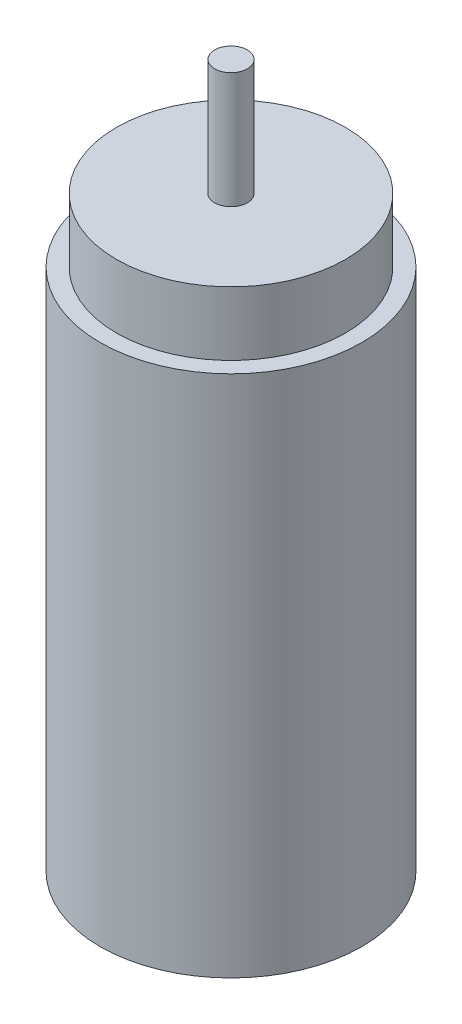
SolidWorks part; units mm, degrees
material "Vanadium"
ref_plane "Plan de face" through (0, 0, 0) normal (0, 0, 1) x (1, 0, 0)
ref_plane "Plan de dessus" through (0, 0, 0) normal (0, 1, 0) x (1, 0, 0)
ref_plane "Plan de droite" through (0, 0, 0) normal (1, 0, 0) x (0, 0, -1)
sketch "Sketch1" plane through (0, 0, 0) normal (0, 1, 0) x (1, 0, 0)
  circle A0 centre (0, 0) radius 4
  dimension "D1" = 8
extrude "Boss-Extrude1" add sketch "Sketch1" along normal blind 16
sketch "Sketch2" plane through (0, 16, 0) normal (0, 1, 0) x (1, 0, 0)
  circle A0 centre (0, 0) radius 3.5
  dimension "D1" = 7
extrude "Boss-Extrude2" add sketch "Sketch2" along normal blind 1.95
sketch "Sketch4" plane through (0, 16, 0) normal (0, 1, 0) x (1, 0, 0)
  circle A0 centre (0, 0) radius 0.5
  dimension "D1" = 1
extrude "Boss-Extrude3" add sketch "Sketch4" along normal blind 5.5
ref_point "Point1"
